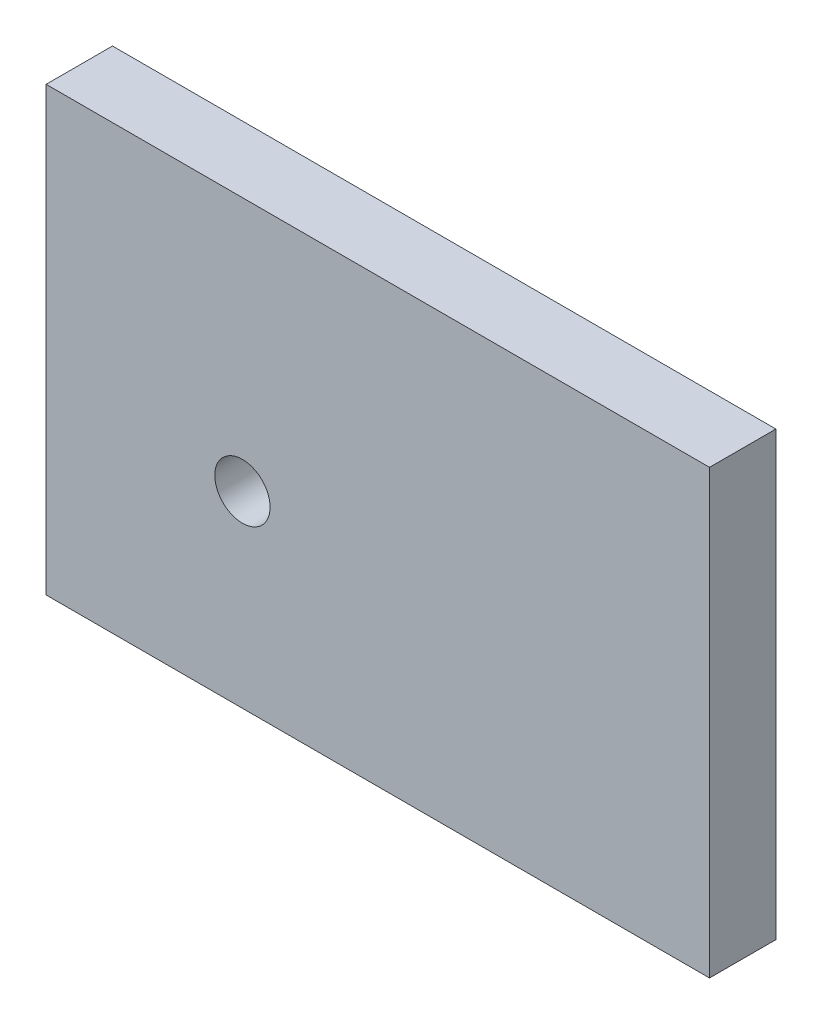
SolidWorks part; units mm, degrees
ref_plane "Plan de face" through (0, 0, 0) normal (0, 0, 1) x (1, 0, 0)
ref_plane "Plan de dessus" through (0, 0, 0) normal (0, 1, 0) x (1, 0, 0)
ref_plane "Plan de droite" through (0, 0, 0) normal (1, 0, 0) x (0, 0, -1)
sketch "Esquisse1" plane through (0, 0, 0) normal (0, 0, 1) x (1, 0, 0)
  line L1 (0, 0) -> (-60, 0)
  line L2 (0, 0) -> (0, 40)
  line L3 (0, 40) -> (-60, 40)
  line L4 (-60, 0) -> (-60, 40)
  dimension "D1" = 60
  dimension "D2" = 40
extrude "Boss.-Extru.1" add sketch "Esquisse1" along normal blind 6
sketch "Esquisse2" plane through (0, 0, 0) normal (0, 0, -1) x (-1, 0, 0)
  line L0 (60, 0) -> (0, 0) construction
  circle A0 centre (42.2455, 17) radius 2.5
  dimension "D1" = 5
  dimension "D2" = 17
extrude "Enlèv. mat.-Extru.1" cut sketch "Esquisse2" against normal blind 10
